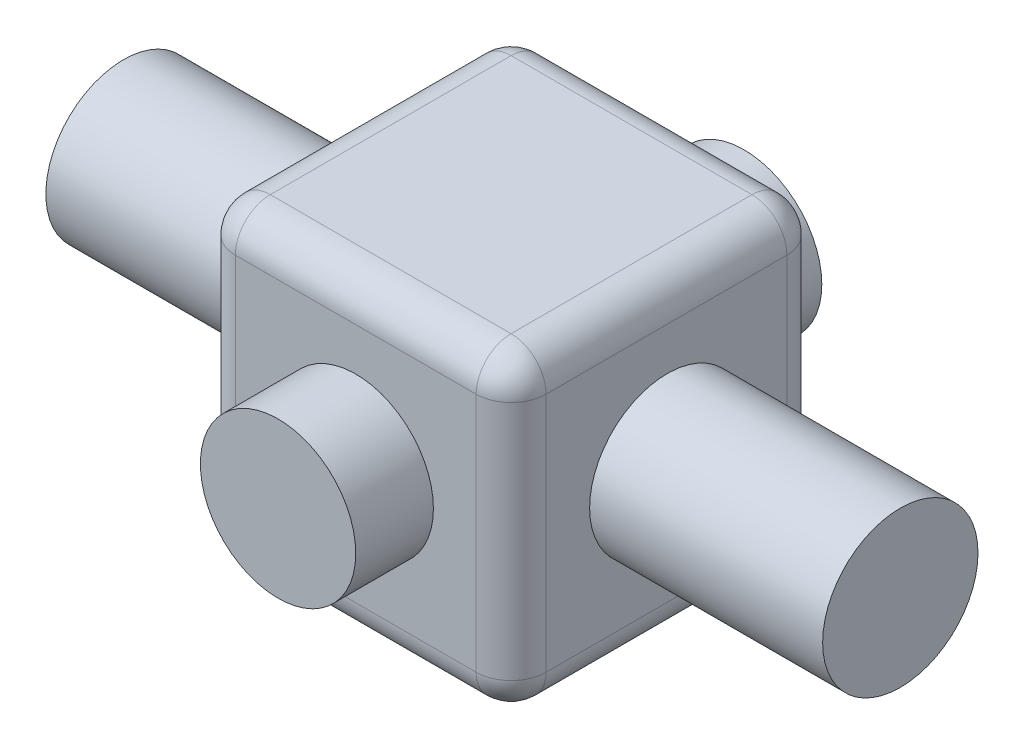
SolidWorks part; units mm, degrees
ref_plane "Front Plane" through (0, 0, 0) normal (0, 0, 1) x (1, 0, 0)
ref_plane "Top Plane" through (0, 0, 0) normal (0, 1, 0) x (1, 0, 0)
ref_plane "Right Plane" through (0, 0, 0) normal (1, 0, 0) x (0, 0, -1)
sketch "Sketch1" plane through (0, 0, 0) normal (0, 0, 1) x (1, 0, 0)
  line L1 (4, -4) -> (-4, -4)
  line L2 (4, -4) -> (4, 4)
  line L3 (4, 4) -> (-4, 4)
  line L4 (-4, -4) -> (-4, 4)
  line L5 (4, -4) -> (-4, 4) construction
  line L6 (4, 4) -> (-4, -4) construction
  point P0 (0, 0)
  dimension "D1" = 8
  dimension "D2" = 8
extrude "Boss-Extrude1" add sketch "Sketch1" along normal blind 8
fillet "Fillet1" radius 0.9 12 edges at (0, -4, 0) (-4, 0, 0) (-4, 4, 4) (-4, -4, 4) (0, -4, 8) (-4, 0, 8) (0, 4, 0) (0, 4, 8) (4, -4, 4) (4, 0, 0) (4, 4, 4) (4, 0, 8)
sketch "Sketch2" plane through (0, 0, 8) normal (0, 0, 1) x (1, 0, 0)
  circle A0 centre (0, 0) radius 2
  dimension "D1" = 4
extrude "Boss-Extrude2" add sketch "Sketch2" along normal blind 2 and the other way blind 10
sketch "Sketch3" plane through (4, 0, 0) normal (1, 0, 0) x (0, 0, -1)
  circle A0 centre (-3.9786, 0) radius 2
  dimension "D1" = 4
sketch "Sketch4" plane through (0, 0, 0) normal (1, 0, 0) x (0, 0, -1)
  circle A0 centre (-3.9786, 0) radius 2
  dimension "D1" = 4
extrude "Boss-Extrude6" add sketch "Sketch4" along normal mid plane 20
